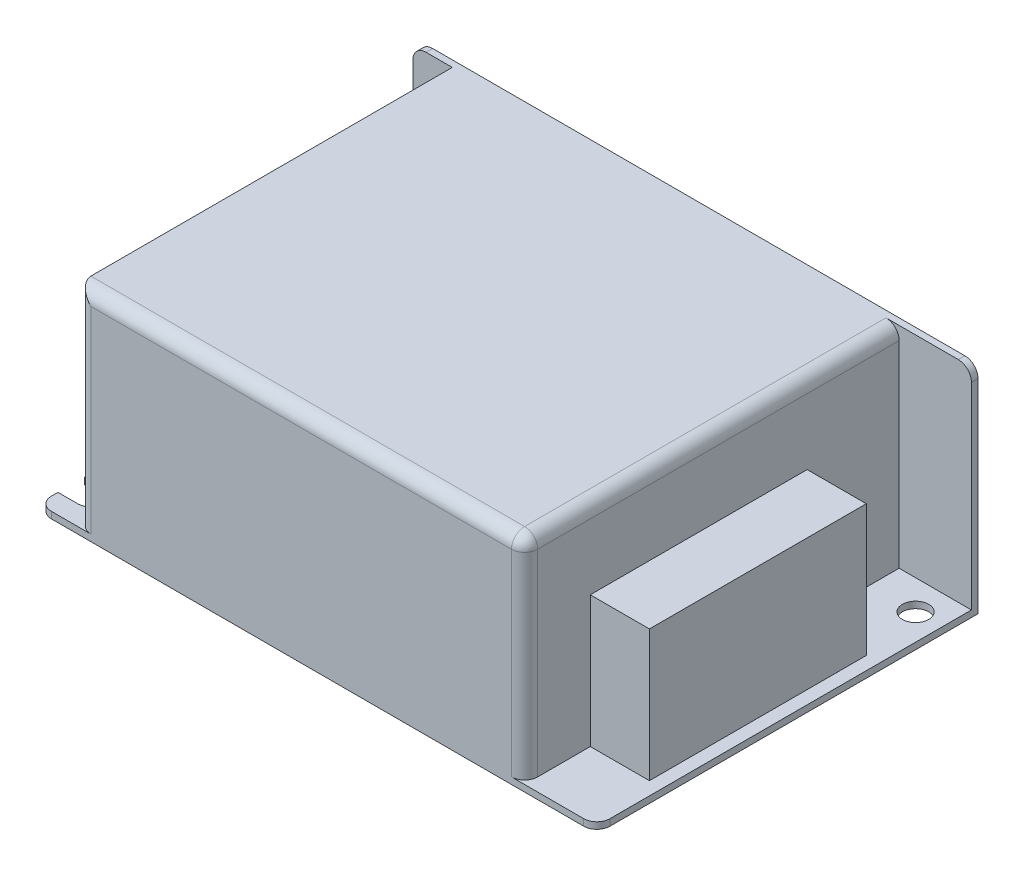
SolidWorks part; units mm, degrees
ref_plane "Front Plane" through (0, 0, 0) normal (0, 0, 1) x (1, 0, 0)
ref_plane "Top Plane" through (0, 0, 0) normal (0, 1, 0) x (1, 0, 0)
ref_plane "Right Plane" through (0, 0, 0) normal (1, 0, 0) x (0, 0, -1)
sketch "Sketch1" plane through (0, 0, 0) normal (0, 1, 0) x (1, 0, 0)
  line L1 (-42.5, -29) -> (42.5, -29)
  line L2 (-42.5, -29) -> (-42.5, 29)
  line L3 (-42.5, 29) -> (42.5, 29)
  line L4 (42.5, -29) -> (42.5, 29)
  line L5 (-42.5, -29) -> (42.5, 29) construction
  line L6 (-42.5, 29) -> (42.5, -29) construction
  point P0 (0, 0)
  dimension "D1" = 85
  dimension "D2" = 58
extrude "Boss-Extrude1" add sketch "Sketch1" along normal blind 33
sketch "Sketch2" plane through (0, 33, 0) normal (0, 1, 0) x (1, 0, 0)
  line L0 (42.5, 29) -> (-42.5, 29) construction
  line L1 (42.5, -29) -> (31.5, -29)
  line L2 (42.5, -29) -> (42.5, 28)
  line L3 (42.5, 28) -> (31.5, 28)
  line L4 (31.5, -29) -> (31.5, 28)
  dimension "D1" = 11
  dimension "D2" = 1
extrude "Cut-Extrude1" cut sketch "Sketch2" against normal offset from surface (32 mm away) 1 up to face at (0, 0, 0)
sketch "Sketch3" plane through (0, 33, 0) normal (0, 1, 0) x (1, 0, 0)
  line L0 (42.5, 29) -> (-42.5, 29) construction
  line L1 (-42.5, -29) -> (-36.5, -29)
  line L2 (-42.5, -29) -> (-42.5, 28)
  line L3 (-42.5, 28) -> (-36.5, 28)
  line L4 (-36.5, -29) -> (-36.5, 28)
  dimension "D1" = 6
  dimension "D2" = 1
extrude "Cut-Extrude2" cut sketch "Sketch3" against normal offset from surface (32 mm away) 1 up to face at (0, 0, 0)
sketch "Sketch4" plane through (0, 1, 0) normal (0, 1, 0) x (1, 0, 0)
  line L0 (31.5, 28) -> (31.5, -29) construction
  line L1 (31.5, -19) -> (40.5, -19)
  line L2 (31.5, -19) -> (31.5, 14)
  line L3 (31.5, 14) -> (40.5, 14)
  line L4 (40.5, -19) -> (40.5, 14)
  line L5 (42.5, -29) -> (42.5, 28) construction
  line L6 (31.5, -29) -> (42.5, -29) construction
  dimension "D1" = 33
  dimension "D2" = 2
  dimension "D3" = 10
extrude "Boss-Extrude2" add sketch "Sketch4" along normal blind 20
sketch "Sketch5" plane through (0, 0, 0) normal (0, -1, 0) x (1, 0, 0)
  line L0 (38.5, -23.5) -> (40.5, -23.5)
  line L1 (42.5, 29) -> (42.5, -29) construction
  line L2 (38.5, -23.5) -> (38.5, -25.5)
  line L3 (42.5, -29) -> (-42.5, -29) construction
  line L4 (-39.5, 24) -> (-42.5, 24) construction
  line L5 (-42.5, -29) -> (-42.5, 29) construction
  line L6 (-39.5, 22) -> (-42.5, 22)
  line L7 (-39.5, 26) -> (-42.5, 26)
  line L8 (-42.5, 29) -> (42.5, 29) construction
  line L9 (-39.5, 24) -> (-37.5, 24)
  circle A0 centre (38.5, -23.5) radius 2
  arc A1 (-39.5, 22) -> (-39.5, 26) centre (-39.5, 24) ccw
  arc A2 (-42.5, 26) -> (-42.5, 22) centre (-42.5, 24) ccw
  point P12 (-41, 24)
  dimension "D1" = 4
  dimension "D2" = 2
  dimension "D3" = 3.5
  dimension "D4" = 3
  dimension "D5" = 5
  dimension "D6" = 4
extrude "Cut-Extrude3" cut sketch "Sketch5" against normal up to next contours L0 A0 L2 | L2 A0 L0 | L6 A2 L7 A1
fillet "Fillet1" radius 2 8 edges at (42.5, 0.5, 29) (-42.5, 0.5, 29) (-36.5, 17, 29) (31.5, 17, 29) (-2.5, 33, 29) (31.5, 33, 0.5) (-42.5, 33, -28.5) (42.5, 33, -28.5)
